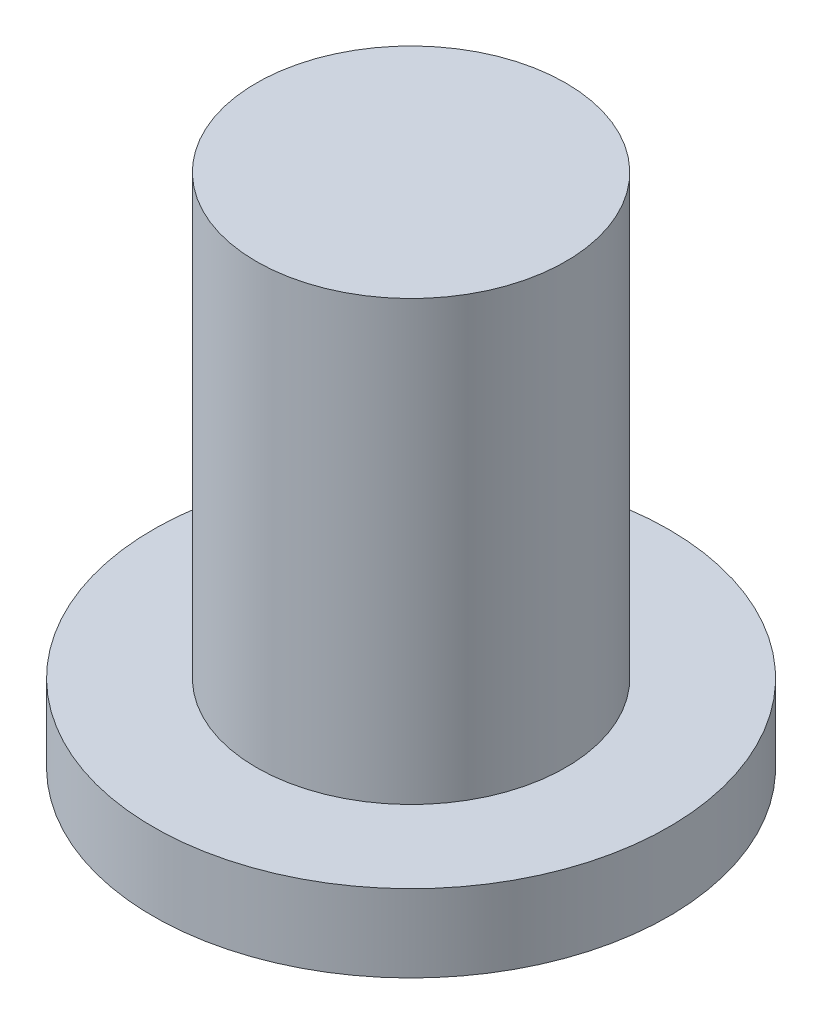
SolidWorks part; units mm, degrees
ref_plane "前视基准面" through (0, 0, 0) normal (0, 0, 1) x (1, 0, 0)
ref_plane "上视基准面" through (0, 0, 0) normal (0, 1, 0) x (1, 0, 0)
ref_plane "右视基准面" through (0, 0, 0) normal (1, 0, 0) x (0, 0, -1)
other "Configuration Table"
sketch "草图1" plane through (0, 0, 0) normal (0, 1, 0) x (1, 0, 0)
  circle A0 centre (0, 0) radius 6
  dimension "D1" = 12
extrude "凸台-拉伸1" add sketch "草图1" along normal blind 17
sketch "草图2" plane through (0, 0, 0) normal (0, -1, 0) x (1, 0, 0)
  circle A0 centre (0, 0) radius 10
  dimension "D1" = 20
extrude "凸台-拉伸2" add sketch "草图2" along normal blind 3
